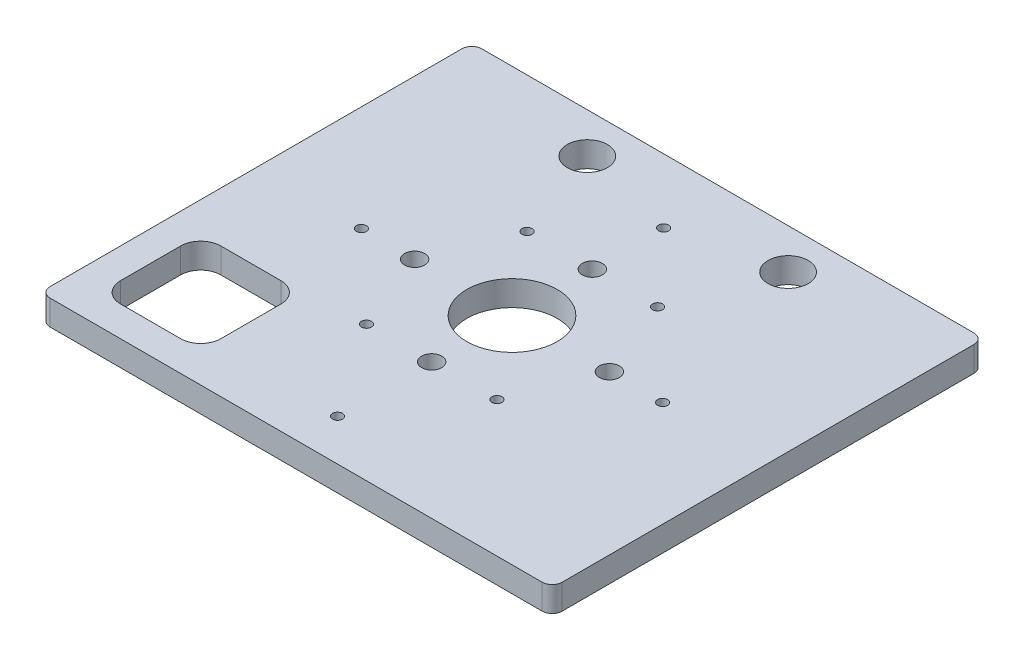
SolidWorks part; units mm, degrees
ref_plane "Front Plane" through (0, 0, 0) normal (0, 0, 1) x (1, 0, 0)
ref_plane "Top Plane" through (0, 0, 0) normal (0, 1, 0) x (1, 0, 0)
ref_plane "Right Plane" through (0, 0, 0) normal (1, 0, 0) x (0, 0, -1)
sketch "Sketch1" plane through (0, 0, 0) normal (0, 1, 0) x (1, 0, 0)
  line L0 (-9.7, 0) -> (9.7, 0)
  line L1 (-25.5, -21.5) -> (25.5, -21.5)
  line L2 (-25.5, -21.5) -> (-25.5, 21.5)
  line L3 (-25.5, 21.5) -> (25.5, 21.5)
  line L4 (25.5, -21.5) -> (25.5, 21.5)
  line L6 (-25.5, 21.5) -> (25.5, -21.5) construction
  line L7 (-28.05, 0) -> (28.05, 0) construction
  line L8 (0, -8) -> (0, 8)
  line L9 (0, -23.65) -> (0, 23.65) construction
  line L10 (-10, 21.5) -> (-10, 17.5)
  line L11 (-10, 17.5) -> (0, 17.5)
  line L13 (-20.5, -18.5) -> (-14.5, -18.5)
  line L14 (-22.5, -16.5) -> (-22.5, -10.5)
  line L15 (-20.5, -8.5) -> (-14.5, -8.5)
  line L16 (-12.5, -16.5) -> (-12.5, -10.5)
  circle A0 centre (0, 0) radius 4.5
  circle A1 centre (9.7, 0) radius 1
  circle A2 centre (-9.7, 0) radius 1
  circle A3 centre (0, 8) radius 1
  circle A4 centre (0, -8) radius 1
  circle A5 centre (-10, 17.5) radius 2
  circle A6 centre (10, 17.5) radius 2
  arc A7 (-12.5, -16.5) -> (-14.5, -18.5) centre (-14.5, -16.5) cw
  arc A8 (-20.5, -18.5) -> (-22.5, -16.5) centre (-20.5, -16.5) cw
  arc A9 (-20.5, -8.5) -> (-22.5, -10.5) centre (-20.5, -10.5) ccw
  arc A10 (-14.5, -8.5) -> (-12.5, -10.5) centre (-14.5, -10.5) cw
  circle A11 centre (-15, 0) radius 0.5
  circle A12 centre (15, 0) radius 0.5
  circle A13 centre (0, -17.3753) radius 0.5
  circle A14 centre (0, 15.1037) radius 0.5
  circle A15 centre (6.5, 8) radius 0.5
  circle A16 centre (-6.5, 8) radius 0.5
  circle A17 centre (-6.5, -8) radius 0.5
  circle A18 centre (6.5, -8) radius 0.5
  point P0 (0, 0)
  point P13 (0, 0)
  point P19 (0, 0)
  point P28 (-19.3945, -16.3522)
  point P37 (-22.5, -18.5)
  point P40 (-22.5, -8.5)
  point P43 (-12.5, -8.5)
  point P60 (0, 0)
  dimension "D3" = 19.4
  dimension "D5" = 10
  dimension "D7" = 10
  dimension "D11" = 2
  dimension "D12" = 30
  dimension "D1" = 51
  dimension "D2" = 43
  dimension "D4" = 16
  dimension "D6" = 4
  dimension "D8" = 3
  dimension "D9" = 10
  dimension "D10" = 3
  dimension "D13" = 15
  dimension "D14" = 13
  dimension "D15" = 6.5
  dimension "D16" = 8
  dimension "D17" = 16
  dimension "D18" = 16
  dimension "D19" = 13
  dimension "D20" = 6.5
extrude "Boss-Extrude1" add sketch "Sketch1" along normal blind 2.5
fillet "Fillet1" radius 1 4 edges at (25.5, 1.25, 21.5) (25.5, 1.25, -21.5) (-25.5, 1.25, -21.5) (-25.5, 1.25, 21.5)
